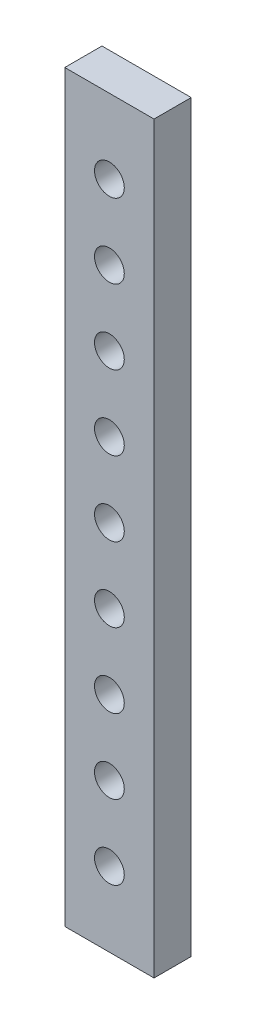
SolidWorks part; units mm, degrees
ref_plane "Front Plane" through (0, 0, 0) normal (0, 0, 1) x (1, 0, 0)
ref_plane "Top Plane" through (0, 0, 0) normal (0, 1, 0) x (1, 0, 0)
ref_plane "Right Plane" through (0, 0, 0) normal (1, 0, 0) x (0, 0, -1)
sketch "Sketch1" plane through (0, 0, 0) normal (0, 0, 1) x (1, 0, 0)
  line L1 (-6, 50) -> (6, 50)
  line L2 (-6, 50) -> (-6, -50)
  line L3 (-6, -50) -> (6, -50)
  line L4 (6, 50) -> (6, -50)
  line L5 (-6, 50) -> (6, -50) construction
  line L6 (-6, -50) -> (6, 50) construction
  circle A0 centre (0, 0) radius 2
  circle A1 centre (0, 10) radius 2
  circle A2 centre (0, 20) radius 2
  circle A3 centre (0, 30) radius 2
  circle A4 centre (0, 40) radius 2
  circle A5 centre (0, -10) radius 2
  circle A6 centre (0, -20) radius 2
  circle A7 centre (0, -30) radius 2
  circle A8 centre (0, -40) radius 2
  point P0 (0, 0)
  dimension "D3" = 4
  dimension "D1" = 12
  dimension "D2" = 100
  dimension "D4" = 5
  dimension "D5" = 5
extrude "Boss-Extrude1" add sketch "Sketch1" along normal blind 5
